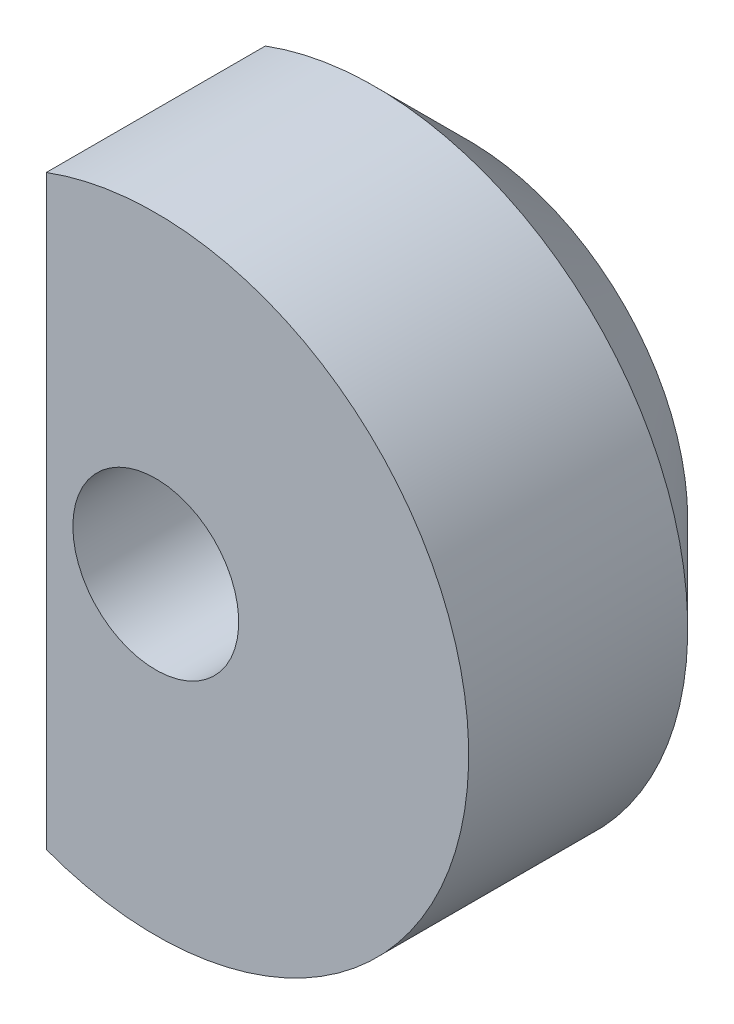
SolidWorks part; units mm, degrees
ref_plane "Front Plane" through (0, 0, 0) normal (0, 0, 1) x (1, 0, 0)
ref_plane "Top Plane" through (0, 0, 0) normal (0, 1, 0) x (1, 0, 0)
ref_plane "Right Plane" through (0, 0, 0) normal (1, 0, 0) x (0, 0, -1)
sketch "Sketch1" plane through (0, 0, 0) normal (0, 0, 1) x (1, 0, 0)
  line L0 (-3.5, 9.3675) -> (-3.5, -9.3675)
  arc A0 (-3.5, -9.3675) -> (-3.5, 9.3675) centre (0, 0) ccw
  dimension "D1" = 10
  dimension "D2" = 3.5
extrude "Boss-Extrude1" add sketch "Sketch1" along normal blind 10
hole_wizard "CBORE for M5 Hex Head Bolt1" positions "Sketch2" profile "Sketch3" counterbore size "M5" standard "ANSI Metric" end condition through all
sketch "Sketch2" plane through (0, 0, 0) normal (0, 0, -1) x (-1, 0, 0)
  point P0 (0, 0)
sketch "Sketch3" plane through (0, 0, 0) normal (1, 0, 0) x (0, 1, 0)
  line L0 (0, 0) -> (0, 10)
  line L1 (0, 10) -> (2.65, 10)
  line L3 (2.65, 10) -> (2.65, 3.58)
  line L4 (2.65, 3.58) -> (6.12, 3.58)
  line L5 (6.12, 3.58) -> (6.12, 0)
  line L7 (6.12, 0) -> (0, 0)
  line L11 (0, -6.35) -> (0, 107.95) construction
  dimension "Thru Hole Dia." = 5.3
  dimension "Thru Hole Depth" = 10
  dimension "C'Bore Dia." = 12.24
  dimension "C'Bore Depth" = 3.58
chamfer "Chamfer1" distance 3 angle 45 1 edges at (10, 0, 0)
